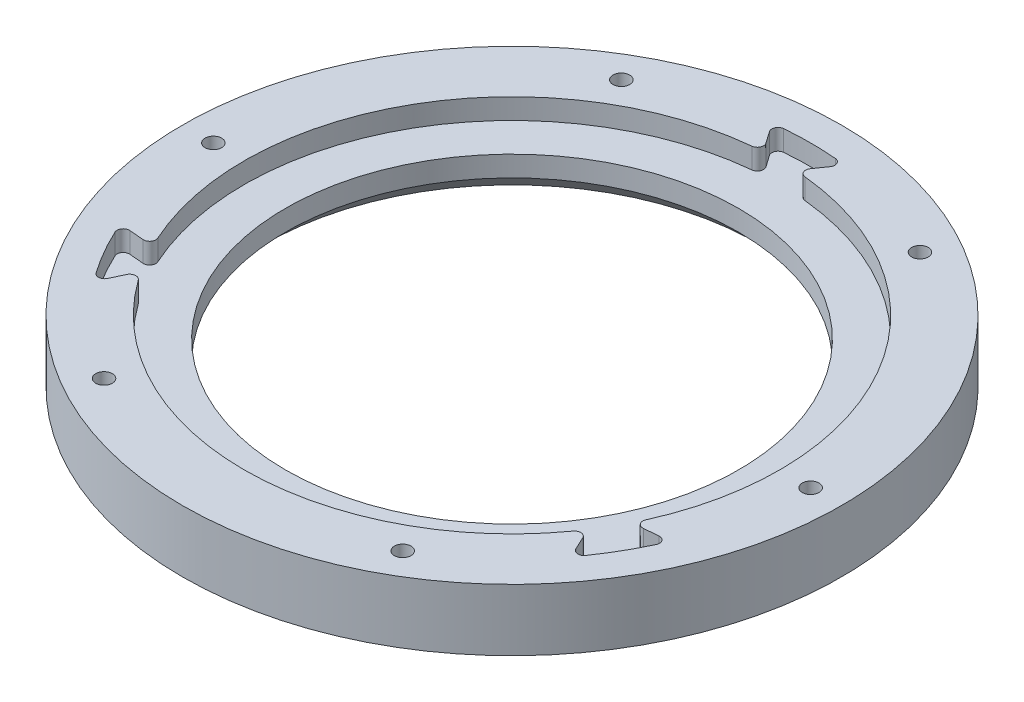
SolidWorks part; units mm, degrees
ref_plane "Front Plane" through (0, 0, 0) normal (0, 0, 1) x (1, 0, 0)
ref_plane "Top Plane" through (0, 0, 0) normal (0, 1, 0) x (1, 0, 0)
ref_plane "Right Plane" through (0, 0, 0) normal (1, 0, 0) x (0, 0, -1)
sketch "Sketch2" plane through (0, 0, 0) normal (1, 0, 0) x (0, 0, -1)
  line L0 (-55, 0) -> (-80, 0)
  line L1 (-80, 0) -> (-80, 15)
  line L2 (-80, 15) -> (-65, 15)
  line L3 (-65, 15) -> (-65, 10)
  line L4 (-65, 10) -> (-55, 10)
  line L5 (-55, 10) -> (-55, 0)
  point P3 (0, 0)
  point P8 (-21.7404, 0)
  point P9 (-22.787, 8.087)
  dimension "D1" = 80
  dimension "D2" = 15
  dimension "D3" = 5
  dimension "D4" = 15
  dimension "D5" = 10
ref_axis "Axis1" through (0, -0.75, 0) along (0, 1, 0)
revolve "Revolve1" add sketch "Sketch2" angle 360 about axis through (0, -0.75, 0) along (0, 1, 0)
sketch "Sketch4" plane through (0, 15, 0) normal (0, 1, 0) x (1, 0, 0)
  line L0 (0, 0) -> (0, 84.4218) construction
  line L1 (-3.8812, 64.884) -> (-8.8355, 71.9596)
  line L2 (8.8355, 71.9596) -> (3.8812, 64.884)
  line L3 (-3.8812, 64.884) -> (0, 59.3412) construction
  line L4 (0, 0) -> (-8.8355, 71.9596) construction
  arc A0 (-3.8812, 64.884) -> (3.8812, 64.884) centre (0, 0) cw
  circle A1 centre (0, 0) radius 65 construction
  arc A2 (-8.8355, 71.9596) -> (8.8355, 71.9596) centre (0, 0) cw
  point P6 (9.3064, 58.6069)
  dimension "D1" = 35
  dimension "D2" = 7.5
  dimension "D3" = 7
extrude "Cut-Extrude1" cut sketch "Sketch4" against normal blind 5
fillet "Fillet1" radius 1.5 4 edges at (8.8355, 12.5, -71.9596) (3.8812, 12.5, -64.884) (-8.8355, 12.5, -71.9596) (-3.8812, 12.5, -64.884)
chamfer "Chamfer1" distance 5 angle 45 1 edges at (0, 0, -55)
pattern_circular "CirPattern2" count 3 over 360 about axis through (0, 0, 0) along (0, 1, 0) of "Cut-Extrude1", "Fillet1"
hole_wizard "#10-32 Tapped Hole1" positions "Sketch6" profile "Sketch7" tap size "#10-32" standard "ANSI Inch"
sketch "Sketch6" plane through (0, 15, 0) normal (0, 1, 0) x (1, 0, 0)
  line L0 (0, 0) -> (-69.8201, 120.932) construction
  line L2 (0, 0) -> (0, 109.0908) construction
  point P0 (-36.25, 62.7868)
  dimension "D1" = 30
  dimension "D2" = 72.5
sketch "Sketch7" plane through (-36.25, 15, -62.7868) normal (1, 0, 0) x (0, 0, 1)
  line L0 (0, 0) -> (0, 11.2133)
  line L1 (0, 11.2133) -> (2.0193, 10)
  line L2 (2.0193, 10) -> (2.0193, 0)
  line L5 (2.0193, 0) -> (0, 0)
  line L10 (0, 11.2133) -> (-2.0193, 10) construction
  line L11 (0, -6.35) -> (0, 107.95) construction
  dimension "Tap Drill Dia." = 4.0386
  dimension "Tap Drill Depth" = 10
  dimension "Drill Angle" = 118
cosmetic thread "Hole Thread1" parameters "D1"=8, "D2"=4.826
pattern_circular "CirPattern3" count 6 over 360 about axis through (0, 0, 0) along (0, 1, 0) of "#10-32 Tapped Hole1"
